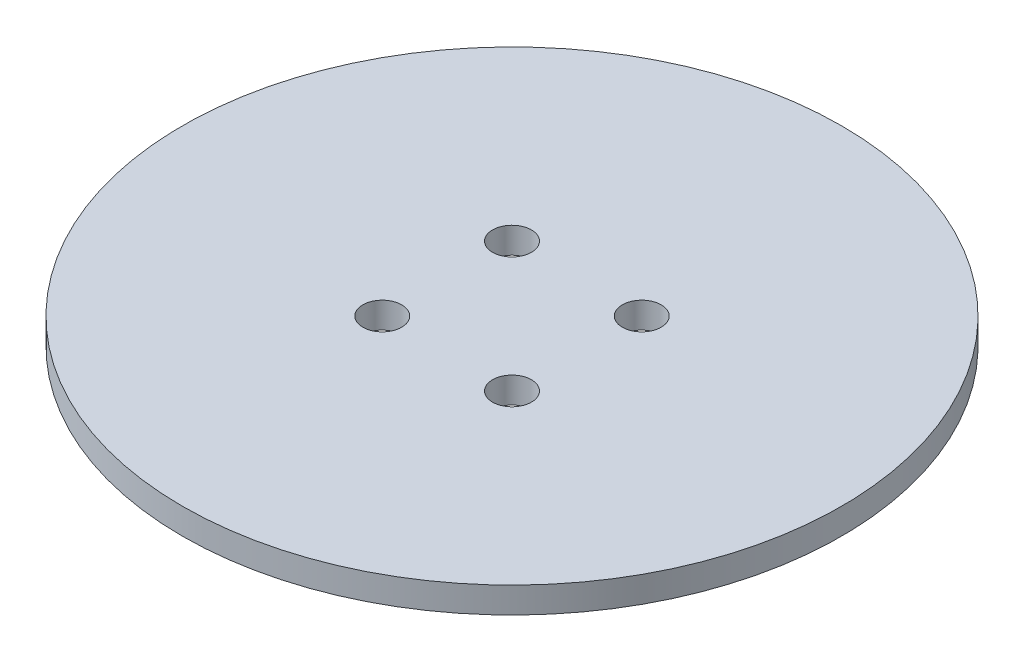
SolidWorks part; units mm, degrees
material "Oak"
ref_plane "Front Plane" through (0, 0, 0) normal (0, 0, 1) x (1, 0, 0)
ref_plane "Top Plane" through (0, 0, 0) normal (0, 1, 0) x (1, 0, 0)
ref_plane "Right Plane" through (0, 0, 0) normal (1, 0, 0) x (0, 0, -1)
sketch "Sketch1" plane through (0, 0, 0) normal (0, 1, 0) x (1, 0, 0)
  circle A0 centre (0, 0) radius 38.1
  dimension "D1" = 76.2
extrude "Boss-Extrude1" add sketch "Sketch1" along normal blind 3
sketch "Sketch3" [suppressed] plane through (0, 3, 0) normal (0, 1, 0) x (1, 0, 0)
  line L0 (0, 0) -> (0, -10)
  line L1 (0, 0) -> (8.6603, 5)
  line L2 (0, 0) -> (-8.6603, 5)
  circle A3 centre (-8.6603, 5) radius 1.5
  circle A4 centre (8.6603, 5) radius 1.5
  circle A5 centre (0, -10) radius 1.5
  dimension "D6" = 3
  dimension "D7" = 3
  dimension "D8" = 3
  dimension "D1" = 10
  dimension "D2" = 10
  dimension "D3" = 10
  dimension "D4" = 120
  dimension "D5" = 120
extrude "Cut-Extrude2" [suppressed] cut sketch "Sketch3" against normal through all contours A5 | A4 | A3
hole_wizard "#8 Clearance Hole1" positions "Sketch4" profile "Sketch5" hole size "#8" standard "ANSI Inch" end condition through all
sketch "Sketch4" plane through (0, 3, 0) normal (0, 1, 0) x (1, 0, 0)
  point P0 (-7.5, 7.5)
  point P2 (7.5, 7.5)
  point P4 (-7.5, -7.5)
  point P6 (7.5, -7.5)
  dimension "D1" = 15
  dimension "D2" = 15
  dimension "D3" = 7.5
  dimension "D4" = 7.5
sketch "Sketch5" plane through (-7.5, 3, -7.5) normal (1, 0, 0) x (0, 0, 1)
  line L0 (0, 0) -> (0, 3)
  line L1 (0, 3) -> (2.2479, 3)
  line L2 (2.2479, 3) -> (2.2479, 0)
  line L5 (2.2479, 0) -> (0, 0)
  line L11 (0, -6.35) -> (0, 107.95) construction
  dimension "Thru Hole Dia." = 4.4958
  dimension "Thru Hole Depth" = 3
equation "\"D3@Sketch4\"=\"D1@Sketch4\"/2"
equation "\"D4@Sketch4\"=\"D2@Sketch4\"/2"
